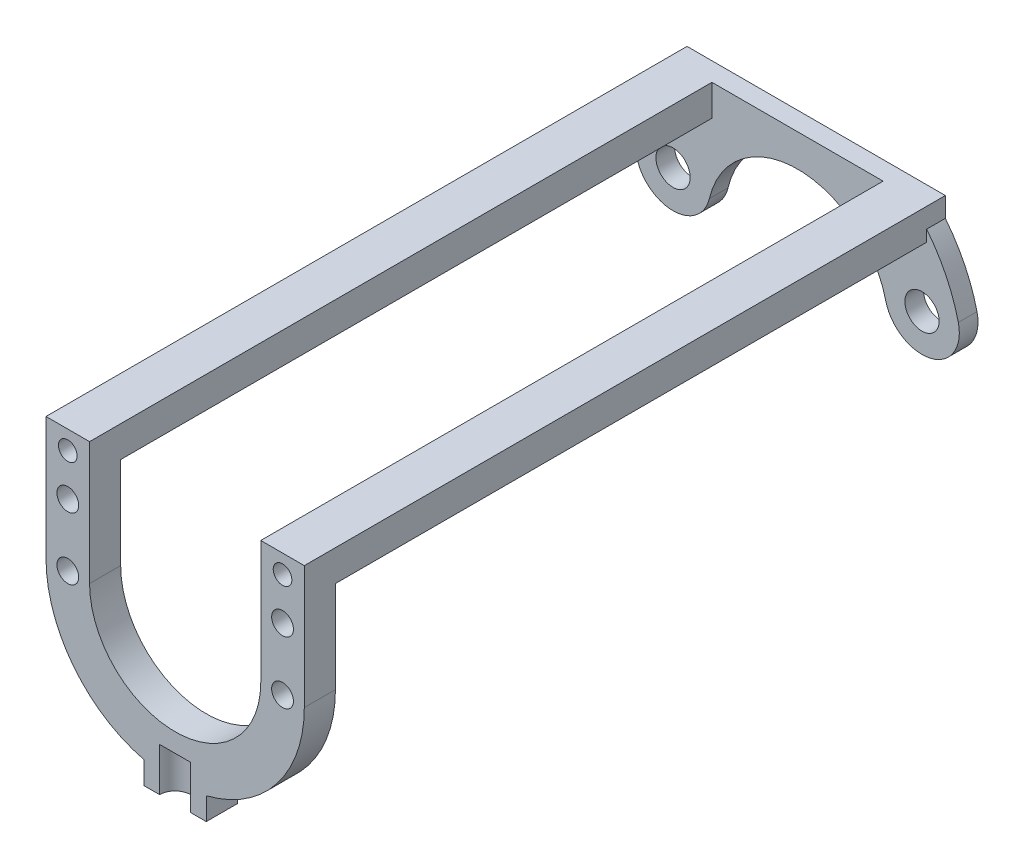
SolidWorks part; units mm, degrees
ref_plane "Front Plane" through (0, 0, 0) normal (0, 0, 1) x (1, 0, 0)
ref_plane "Top Plane" through (0, 0, 0) normal (0, 1, 0) x (1, 0, 0)
ref_plane "Right Plane" through (0, 0, 0) normal (1, 0, 0) x (0, 0, -1)
sketch "Sketch2" plane through (0, 0, 0) normal (0, 0, 1) x (1, 0, 0)
  line L0 (-19, 19.75) -> (-15, 19.75) construction
  line L1 (-17.7532, 19.75) -> (-15, 19.75)
  line L2 (15, 19.75) -> (19, 19.75) construction
  line L3 (15, 19.75) -> (17.7532, 19.75)
  line L4 (-17.7532, 19.75) -> (17.7532, 19.75)
  line L5 (0, 19.75) -> (0, 15.356)
  line L6 (-17.7532, 19.75) -> (-20.7532, 19.75)
  line L7 (17.7532, 19.75) -> (20.7532, 19.75)
  line L8 (20.7532, 19.75) -> (20.7532, 16.5693)
  line L9 (-20.7532, 19.75) -> (-20.7532, 16.5693)
  circle A0 centre (-20, 4.75) radius 6
  circle A1 centre (20, 4.75) radius 6
  arc A2 (14.1624, 3.3636) -> (-14.1624, 3.3636) centre (0, 0) ccw
  arc A3 (25.8376, 6.1364) -> (20.7532, 16.5693) centre (0, 0) ccw
  arc A4 (-20.7532, 16.5693) -> (-25.8376, 6.1364) centre (0, 0) ccw
  circle A5 centre (20, 4.75) radius 2.75 construction
  circle A6 centre (-20, 4.75) radius 2.75 construction
  circle A7 centre (20, 4.75) radius 2.75
  circle A8 centre (-20, 4.75) radius 2.75
  dimension "D1" = 12
  dimension "D2" = 12
  dimension "D3" = 3
  dimension "D4" = 3
extrude "Boss-Extrude1" add sketch "Sketch2" along normal blind 3
sketch "Sketch3" plane through (0, 0, 3) normal (0, 0, 1) x (1, 0, 0)
  line L1 (-20.7532, 19.75) -> (-13.7532, 19.75)
  line L2 (-20.7532, 19.75) -> (-20.7532, 14.75)
  line L3 (-20.7532, 14.75) -> (-13.7532, 14.75)
  line L4 (-13.7532, 19.75) -> (-13.7532, 14.75)
  line L5 (20.7532, 19.75) -> (13.7532, 19.75)
  line L6 (20.7532, 19.75) -> (20.7532, 14.75)
  line L7 (20.7532, 14.75) -> (13.7532, 14.75)
  line L8 (13.7532, 19.75) -> (13.7532, 14.75)
  dimension "D1" = 5
  dimension "D2" = 7
  dimension "D3" = 7
  dimension "D4" = 5
extrude "Boss-Extrude2" add sketch "Sketch3" along normal blind 100
sketch "Sketch4" plane through (0, 0, 103) normal (0, 0, 1) x (1, 0, 0)
  line L0 (13.7532, 19.75) -> (13.7532, 0)
  line L1 (-13.7532, 19.75) -> (-13.7532, 0)
  line L2 (20.7532, 19.75) -> (20.7532, 0)
  line L3 (-20.7532, 19.75) -> (-20.7532, 0)
  line L4 (20.7532, 19.75) -> (13.7532, 19.75) construction
  line L5 (-13.7532, 19.75) -> (-20.7532, 19.75) construction
  line L6 (20.7532, 19.75) -> (13.7532, 19.75)
  line L7 (-13.7532, 19.75) -> (-20.7532, 19.75)
  line L8 (0, -13.7532) -> (0, -23.7532)
  line L9 (-5, -13.7532) -> (-5, -23.7532)
  line L10 (5, -13.7532) -> (5, -23.7532)
  line L11 (-5, -23.7532) -> (5, -23.7532)
  circle A0 centre (0, 0) radius 13.7532
  arc A1 (-20.7532, 0) -> (20.7532, 0) centre (0, 0) ccw
  dimension "D1" = 10
  dimension "D2" = 5
  dimension "D3" = 5
extrude "Boss-Extrude3" add sketch "Sketch4" against normal blind 5
sketch "Sketch5" plane through (0, 0, 103) normal (0, 0, 1) x (1, 0, 0)
  line L0 (13.7532, 0) -> (20.7532, 0)
  line L1 (-13.7532, 0) -> (-20.7532, 0)
  line L2 (0, 0) -> (0, 10)
  line L4 (0, 5) -> (27.8013, 5)
  arc A0 (-20.7532, 0) -> (-5, -20.1419) centre (0, 0) ccw construction
  circle A1 centre (-17.2532, 0) radius 1.75
  circle A2 centre (17.2532, 0) radius 1.75
  circle A3 centre (-17.2532, 10) radius 1.75
  circle A4 centre (17.2532, 10) radius 1.75
  dimension "D1" = 3.5
  dimension "D2" = 3.5
  dimension "D3" = 10
extrude "Cut-Extrude1" cut sketch "Sketch5" against normal blind 5 contours A3 | A4 | L0 A2 | L0 A2 | L1 A1 | L1 A1
sketch "Sketch6" plane through (0, 0, 103) normal (0, 0, 1) x (1, 0, 0)
  line L0 (17.2532, 19.75) -> (17.2532, 16.75)
  line L1 (20.7532, 19.75) -> (13.7532, 19.75) construction
  line L2 (-17.2532, 19.75) -> (-17.2532, 16.75)
  line L3 (-13.7532, 19.75) -> (-20.7532, 19.75) construction
  circle A0 centre (-17.2532, 16.75) radius 1.5
  circle A1 centre (17.2532, 16.75) radius 1.5
  dimension "D3" = 3
  dimension "D4" = 3
  dimension "D1" = 3
  dimension "D2" = 3
extrude "Cut-Extrude2" cut sketch "Sketch6" against normal blind 5
sketch "Sketch7" plane through (0, -23.7532, 0) normal (0, -1, 0) x (1, 0, 0)
  line L0 (-5, 103) -> (5, 103) construction
  circle A0 centre (0, 103) radius 2.5
  dimension "D1" = 5
extrude "Cut-Extrude3" cut sketch "Sketch7" against normal blind 7
